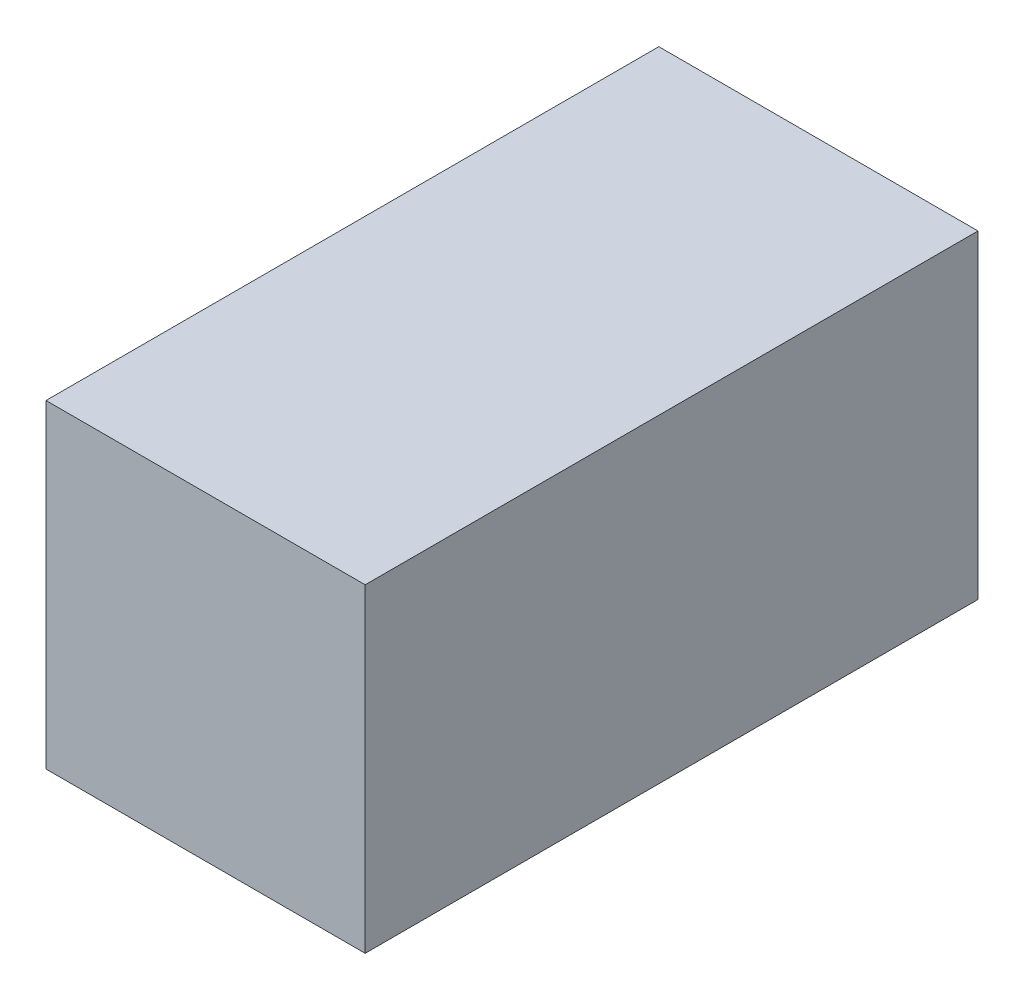
SolidWorks part; units mm, degrees
material "Plain Carbon Steel"
ref_plane "Front Plane" through (0, 0, 0) normal (0, 0, 1) x (1, 0, 0)
ref_plane "Top Plane" through (0, 0, 0) normal (0, 1, 0) x (1, 0, 0)
ref_plane "Right Plane" through (0, 0, 0) normal (1, 0, 0) x (0, 0, -1)
sketch "Sketch1" plane through (0, 0, 0) normal (0, 0, 1) x (1, 0, 0)
  line L0 (-1.1906, 1.1906) -> (1.1906, -1.1906) construction
  line L1 (-1.1906, 1.1906) -> (1.1906, 1.1906)
  line L2 (-1.1906, 1.1906) -> (-1.1906, -1.1906)
  line L3 (-1.1906, -1.1906) -> (1.1906, -1.1906)
  line L4 (1.1906, 1.1906) -> (1.1906, -1.1906)
  dimension "D1" = 2.3813
  dimension "D2" = 2.3813
extrude "Extrude1" add sketch "Sketch1" against normal blind 4.572
